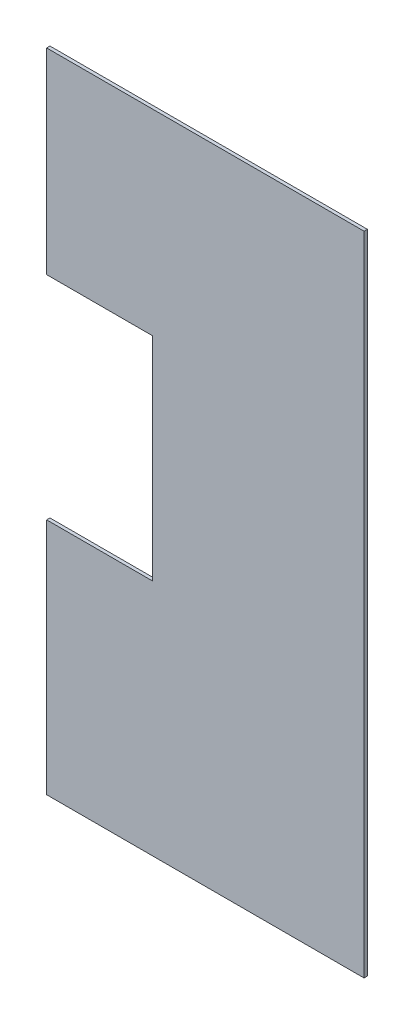
SolidWorks part; units mm, degrees
material "Гипс"
ref_plane "Спереди" through (0, 0, 0) normal (0, 0, 1) x (1, 0, 0)
ref_plane "Сверху" through (0, 0, 0) normal (0, 1, 0) x (1, 0, 0)
ref_plane "Справа" through (0, 0, 0) normal (1, 0, 0) x (0, 0, -1)
sketch "Эскиз1" plane through (0, 0, 0) normal (0, 0, 1) x (1, 0, 0)
  line L1 (0, 0) -> (-1200, 0)
  line L2 (0, 0) -> (0, 2445)
  line L3 (0, 2445) -> (-1200, 2445)
  line L4 (-1200, 0) -> (-1200, 2445)
  dimension "D1" = 1200
  dimension "D2" = 2445
extrude "Бобышка-Вытянуть1" add sketch "Эскиз1" against normal blind 12.5
sketch "Эскиз2" [suppressed] plane through (0, 0, -12.5) normal (0, 0, -1) x (-1, 0, 0)
  line L1 (600, 2090.75) -> (1200, 2090.75)
  line L2 (600, 2090.75) -> (600, 0)
  line L3 (600, 0) -> (1200, 0)
  line L4 (1200, 2090.75) -> (1200, 0)
extrude "Вырез-Вытянуть1" [suppressed] cut sketch "Эскиз2" against normal through all
sketch "Эскиз3" plane through (0, 0, 0) normal (0, 0, 1) x (1, 0, 0)
  line L0 (-1200, 2445) -> (-1200, 0) construction
  line L1 (-800, 1702.75) -> (-1200, 1702.75)
  line L2 (-800, 1702.75) -> (-800, 900)
  line L3 (-800, 900) -> (-1200, 900)
  line L4 (-1200, 1702.75) -> (-1200, 900)
  line L5 (-800, 900) -> (-1600, 900) construction
extrude "Вырез-Вытянуть2" cut sketch "Эскиз3" against normal through all
sketch "Эскиз4" [suppressed] plane through (0, 0, 0) normal (0, 0, 1) x (1, 0, 0)
  line L0 (0, 0) -> (0, 2445) construction
  line L1 (-50, 1700) -> (0, 1700)
  line L2 (-50, 1700) -> (-50, 900)
  line L3 (-50, 900) -> (0, 900)
  line L4 (0, 1700) -> (0, 900)
  line L5 (-50, 900) -> (1550, 900) construction
  line L7 (-50, 1700) -> (-50, 900) construction
extrude "Вырез-Вытянуть3" [suppressed] cut sketch "Эскиз4" against normal through all
sketch "Эскиз5" [suppressed] plane through (0, 0, 0) normal (0, 0, 1) x (1, 0, 0)
  line L0 (-1200, 2445) -> (-1200, 0) construction
  line L1 (0, 1700) -> (-1200, 1700)
  line L2 (0, 1700) -> (0, 900)
  line L3 (0, 900) -> (-1200, 900)
  line L4 (-1200, 1700) -> (-1200, 900)
  line L5 (-1250, 900) -> (350, 900) construction
extrude "Вырез-Вытянуть4" [suppressed] cut sketch "Эскиз5" against normal through all
sketch "Эскиз6" [suppressed] plane through (0, 0, 0) normal (0, 0, 1) x (1, 0, 0)
  line L1 (-700, 2091.5) -> (-1200, 2091.5)
  line L2 (-700, 2091.5) -> (-700, 0)
  line L3 (-700, 0) -> (-1200, 0)
  line L4 (-1200, 2091.5) -> (-1200, 0)
extrude "Вырез-Вытянуть5" [suppressed] cut sketch "Эскиз6" against normal through all
sketch "Эскиз7" [suppressed] plane through (0, 0, 0) normal (0, 0, 1) x (1, 0, 0)
  line L0 (0, 2500) -> (-1200, 2500) construction
  line L1 (0, 0) -> (-825, 0)
  line L2 (0, 0) -> (0, 2500)
  line L3 (0, 2500) -> (-825, 2500)
  line L4 (-825, 0) -> (-825, 2500)
  line L5 (-1200, 2500) -> (-1200, 0) construction
  dimension "D1" = 375
extrude "Вырез-Вытянуть6" [suppressed] cut sketch "Эскиз7" against normal through all
